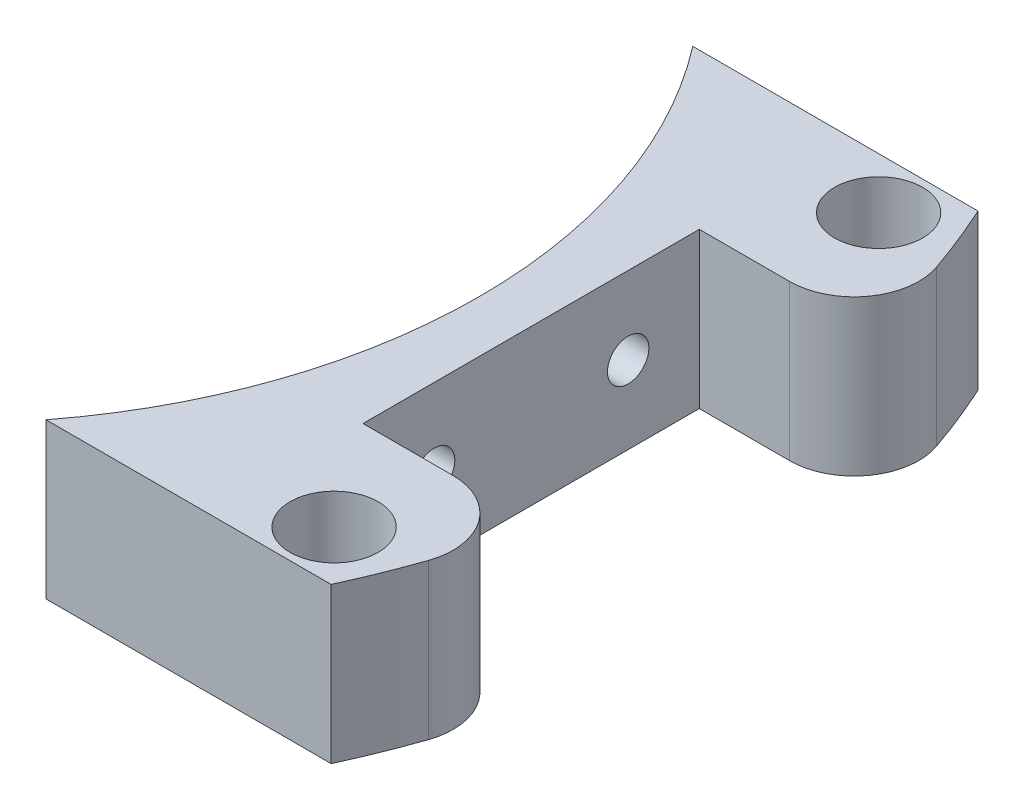
SolidWorks part; units mm, degrees
ref_plane "前视基准面" through (0, 0, 0) normal (0, 0, 1) x (1, 0, 0)
ref_plane "上视基准面" through (0, 0, 0) normal (0, 1, 0) x (1, 0, 0)
ref_plane "右视基准面" through (0, 0, 0) normal (1, 0, 0) x (0, 0, -1)
other "Configuration Table"
sketch "草图1" plane through (0, 0, 0) normal (0, 1, 0) x (1, 0, 0)
  line L3 (98.223, -107.4405) -> (93.8568, -95.4444)
  line L4 (-40.4497, 75.7097) -> (22.0464, 75.7097)
  line L5 (-7.9536, 50.7097) -> (22.0464, 50.7097)
  line L6 (-7.9536, 50.7097) -> (-7.9536, 100.7097)
  line L7 (-7.9536, 100.7097) -> (22.0464, 100.7097)
  line L8 (22.0464, 50.7097) -> (22.0464, 100.7097)
  circle A3 centre (-40.4497, 75.7097) radius 30
  circle A13 centre (10.3636, 96.7573) radius 3.4
  circle A14 centre (10.3636, 54.6621) radius 3.4
  circle A15 centre (-40.4497, 75.7097) radius 41
  circle A16 centre (-40.4497, 75.7097) radius 60
  dimension "D1" = 60
  dimension "D2" = 6.8
  dimension "D8" = 82
  dimension "D11" = 120
  dimension "D3" = 10.3636
  dimension "D4" = 40.4497
  dimension "D5" = 54.6621
  dimension "D6" = 75.7097
  dimension "D7" = 96.7573
  dimension "D9" = 50
  dimension "D10" = 30
extrude "凸台-拉伸2" add sketch "草图1" along normal blind 12 contours A15 L5 L8 L4 A14 | A15 L4 L8 L7 A13
sketch "草图2" plane through (0, 12, 0) normal (0, 1, 0) x (1, 0, 0)
  line L0 (-40.4497, 75.7097) -> (19.5503, 75.7097)
  line L1 (24.5503, 88.7097) -> (4.5503, 88.7097)
  line L2 (24.5503, 88.7097) -> (24.5503, 62.7097)
  line L3 (24.5503, 62.7097) -> (4.5503, 62.7097)
  line L4 (4.5503, 88.7097) -> (4.5503, 62.7097)
  line L6 (-7.9536, 50.7097) -> (14.0938, 50.7097)
  line L7 (14.0938, 100.7097) -> (-7.9536, 100.7097)
  line L8 (-7.9536, 50.7097) -> (14.0938, 50.7097)
  line L9 (14.0938, 100.7097) -> (-7.9536, 100.7097)
  arc A3 (14.0938, 50.7097) -> (14.0938, 100.7097) centre (-40.4497, 75.7097) ccw
  arc A4 (-7.9536, 50.7097) -> (-7.9536, 100.7097) centre (-40.4497, 75.7097) ccw
  arc A5 (14.0938, 50.7097) -> (14.0938, 100.7097) centre (-40.4497, 75.7097) ccw
  arc A6 (-7.9536, 50.7097) -> (-7.9536, 100.7097) centre (-40.4497, 75.7097) ccw
  arc M12 (14.0938, 50.7097) -> (14.0938, 100.7097) centre (-40.4497, 75.7097) ccw
  dimension "D1" = 0
  dimension "D2" = 45
  dimension "D3" = 13
  dimension "D4" = 13
  dimension "D5" = 20
extrude "切除-拉伸1" cut sketch "草图2" against normal through all contours L1 L4 L0 M12 | L0 L4 L3 M12
sketch "草图4" plane through (4.5503, 0, 0) normal (1, 0, 0) x (0, 0, -1)
  line L0 (62.7097, 6) -> (88.7097, 6)
  line L1 (62.7097, 0) -> (62.7097, 12) construction
  line L2 (88.7097, 0) -> (88.7097, 12) construction
  line L3 (75.7097, 12) -> (75.7097, 0)
  line L4 (88.7097, 12) -> (62.7097, 12) construction
  line L5 (88.7097, 0) -> (62.7097, 0) construction
  circle A0 centre (68.2097, 6) radius 1.6
  circle A1 centre (83.2097, 6) radius 1.6
  dimension "D1" = 7.5
  dimension "D2" = 7.5
  dimension "D3" = 3.2
  dimension "D4" = 3.2
extrude "切除-拉伸2" cut sketch "草图4" against normal through all contours L0 A1 | L0 A1 | L0 A0 | L0 A0
ref_plane "基准面1" through (-7.9536, 0, 0) normal (-1, 0, 0) x (0, 0, 1)
sketch "草图6" plane through (-7.9536, 0, 0) normal (-1, 0, 0) x (0, 0, 1)
  circle A0 centre (-83.2097, 6) radius 1.6 construction
  circle A1 centre (-83.2097, 6) radius 1.6
  circle A2 centre (-68.2097, 6) radius 1.6 construction
  circle A3 centre (-68.2097, 6) radius 1.6
  circle A4 centre (-83.2097, 6) radius 3.5
  circle A5 centre (-68.2097, 6) radius 3.5
  dimension "D1" = 7
  dimension "D2" = 7
extrude "切除-拉伸3" cut sketch "草图6" against normal blind 10
fillet "圆角1" radius 5 2 edges at (18.125, 6, -88.7097) (18.125, 6, -62.7097)
